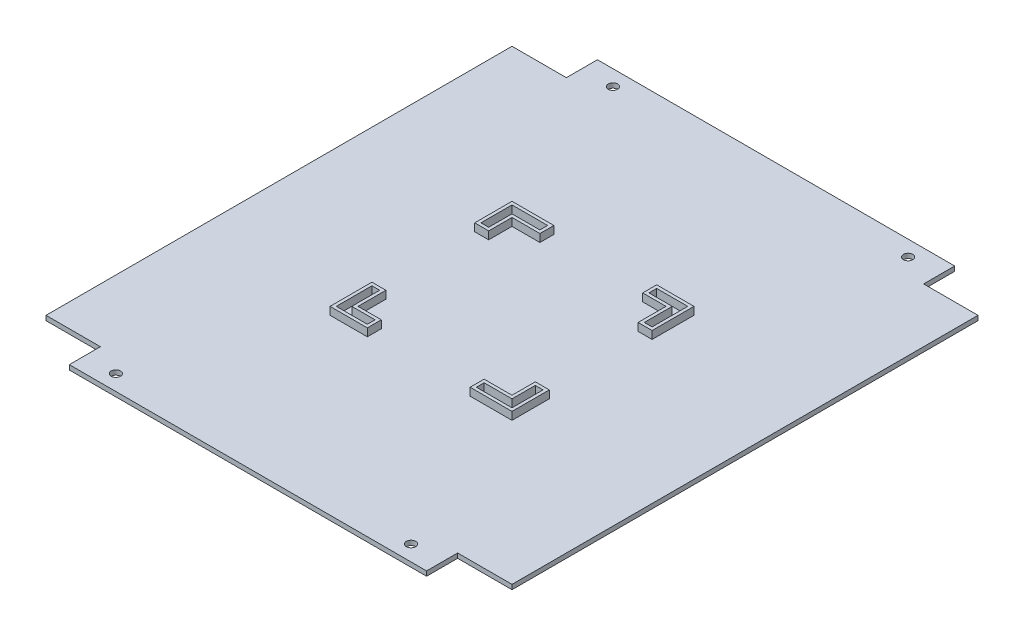
SolidWorks part; units mm, degrees
ref_plane "前视基准面" through (0, 0, 0) normal (0, 0, 1) x (1, 0, 0)
ref_plane "上视基准面" through (0, 0, 0) normal (0, 1, 0) x (1, 0, 0)
ref_plane "右视基准面" through (0, 0, 0) normal (1, 0, 0) x (0, 0, -1)
other "Configuration Table"
sketch "草图1" plane through (0, 0, 0) normal (0, 1, 0) x (1, 0, 0)
  line L0 (285, 0) -> (285, 20)
  line L1 (0, 0) -> (340, 0)
  line L2 (0, 0) -> (0, 340) construction
  line L3 (0, 340) -> (340, 340) construction
  line L4 (340, 0) -> (340, 340)
  line L5 (285, 20) -> (320, 20)
  line L6 (320, 20) -> (320, 55)
  line L7 (320, 55) -> (340, 55) construction
  line L8 (340, 55) -> (340, 0)
  line L9 (0, 170) -> (340, 170) construction
  line L10 (170, 340) -> (170, 0) construction
  line L11 (340, 0) -> (285, 0)
  line L12 (0, 0) -> (55, 0)
  line L13 (0, 55) -> (0, 0)
  line L14 (20, 55) -> (0, 55) construction
  line L15 (20, 20) -> (20, 55)
  line L16 (55, 20) -> (20, 20)
  line L17 (55, 0) -> (55, 20)
  line L18 (55, 340) -> (55, 320)
  line L19 (55, 320) -> (20, 320)
  line L20 (20, 320) -> (20, 285)
  line L21 (20, 285) -> (0, 285) construction
  line L22 (0, 285) -> (0, 340) construction
  line L23 (0, 340) -> (55, 340) construction
  line L24 (340, 340) -> (285, 340) construction
  line L25 (340, 285) -> (340, 340) construction
  line L26 (320, 285) -> (340, 285) construction
  line L27 (320, 320) -> (320, 285)
  line L28 (285, 320) -> (320, 320)
  line L29 (0, 340) -> (340, 340) construction
  line L30 (285, 340) -> (285, 320)
  line L31 (20, 285) -> (20, 55)
  line L32 (320, 285) -> (320, 55)
  line L33 (55, 340) -> (285, 340)
  dimension "D1" = 340
  dimension "D2" = 340
  dimension "D3" = 20
  dimension "D4" = 20
  dimension "D5" = 35
  dimension "D6" = 35
extrude "凸台-拉伸1" add sketch "草图1" along normal blind 3 contours L33 L18 L19 L20 L31 L15 L16 L17 L1 L0 L5 L6 L32 L27 L28 L30
sketch "草图2" plane through (0, 3, 0) normal (0, 1, 0) x (1, 0, 0)
  line L0 (55, 330) -> (285, 330) construction
  line L1 (55, 340) -> (55, 320) construction
  line L2 (285, 340) -> (285, 320) construction
  line L3 (170, 340) -> (170, 0) construction
  line L4 (55, 340) -> (285, 340) construction
  line L5 (55, 0) -> (285, 0) construction
  line L6 (20, 170) -> (320, 170) construction
  line L7 (20, 320) -> (20, 20) construction
  line L8 (320, 20) -> (320, 320) construction
  circle A0 centre (75, 330) radius 3
  circle A1 centre (265, 330) radius 3
  circle A2 centre (265, 10) radius 3
  circle A3 centre (75, 10) radius 3
  dimension "D1" = 6
  dimension "D2" = 20
extrude "切除-拉伸1" cut sketch "草图2" against normal blind 3
sketch "草图3" plane through (0, 3, 0) normal (0, 1, 0) x (1, 0, 0)
  line L0 (20, 170) -> (320, 170) construction
  line L1 (20, 320) -> (20, 20) construction
  line L2 (320, 20) -> (320, 320) construction
  line L3 (170, 340) -> (170, 0) construction
  line L4 (55, 340) -> (285, 340) construction
  line L5 (55, 0) -> (285, 0) construction
  line L6 (170, 170) -> (113.4315, 226.5685) construction
  line L7 (113.4315, 226.5685) -> (113.4315, 206.5685)
  line L8 (113.4315, 226.5685) -> (136.3812, 226.5685)
  line L15 (136.3812, 226.5685) -> (136.3812, 221.5685)
  line L16 (136.3812, 221.5685) -> (118.4315, 221.5685)
  line L17 (118.4315, 221.5685) -> (118.4315, 206.5685)
  line L18 (118.4315, 206.5685) -> (113.4315, 206.5685)
  line L19 (111.4315, 228.5685) -> (111.4315, 204.5685)
  line L20 (120.4315, 204.5685) -> (111.4315, 204.5685)
  line L21 (120.4315, 219.5685) -> (120.4315, 204.5685)
  line L22 (138.3812, 219.5685) -> (120.4315, 219.5685)
  line L23 (138.3812, 228.5685) -> (138.3812, 219.5685)
  line L24 (111.4315, 228.5685) -> (138.3812, 228.5685)
  line L25 (226.5685, 226.5685) -> (206.5685, 226.5685)
  line L26 (226.5685, 226.5685) -> (226.5685, 203.6188)
  line L27 (226.5685, 203.6188) -> (221.5685, 203.6188)
  line L28 (221.5685, 203.6188) -> (221.5685, 221.5685)
  line L29 (221.5685, 221.5685) -> (206.5685, 221.5685)
  line L30 (206.5685, 221.5685) -> (206.5685, 226.5685)
  line L31 (228.5685, 228.5685) -> (204.5685, 228.5685)
  line L32 (204.5685, 219.5685) -> (204.5685, 228.5685)
  line L33 (219.5685, 219.5685) -> (204.5685, 219.5685)
  line L34 (219.5685, 201.6188) -> (219.5685, 219.5685)
  line L35 (228.5685, 201.6188) -> (219.5685, 201.6188)
  line L36 (228.5685, 228.5685) -> (228.5685, 201.6188)
  line L37 (226.5685, 113.4315) -> (226.5685, 133.4315)
  line L38 (226.5685, 113.4315) -> (203.6188, 113.4315)
  line L39 (203.6188, 113.4315) -> (203.6188, 118.4315)
  line L40 (203.6188, 118.4315) -> (221.5685, 118.4315)
  line L41 (221.5685, 118.4315) -> (221.5685, 133.4315)
  line L42 (221.5685, 133.4315) -> (226.5685, 133.4315)
  line L43 (228.5685, 111.4315) -> (228.5685, 135.4315)
  line L44 (219.5685, 135.4315) -> (228.5685, 135.4315)
  line L45 (219.5685, 120.4315) -> (219.5685, 135.4315)
  line L46 (201.6188, 120.4315) -> (219.5685, 120.4315)
  line L47 (201.6188, 111.4315) -> (201.6188, 120.4315)
  line L48 (228.5685, 111.4315) -> (201.6188, 111.4315)
  line L49 (113.4315, 113.4315) -> (133.4315, 113.4315)
  line L50 (113.4315, 113.4315) -> (113.4315, 136.3812)
  line L51 (113.4315, 136.3812) -> (118.4315, 136.3812)
  line L52 (118.4315, 136.3812) -> (118.4315, 118.4315)
  line L53 (118.4315, 118.4315) -> (133.4315, 118.4315)
  line L54 (133.4315, 118.4315) -> (133.4315, 113.4315)
  line L55 (111.4315, 111.4315) -> (135.4315, 111.4315)
  line L56 (135.4315, 120.4315) -> (135.4315, 111.4315)
  line L57 (120.4315, 120.4315) -> (135.4315, 120.4315)
  line L58 (120.4315, 138.3812) -> (120.4315, 120.4315)
  line L59 (111.4315, 138.3812) -> (120.4315, 138.3812)
  line L60 (111.4315, 111.4315) -> (111.4315, 138.3812)
  circle A0 centre (170, 170) radius 80 construction
  dimension "D1" = 5
  dimension "D2" = 2
  dimension "D3" = 5
  dimension "D4" = 4
extrude "凸台-拉伸2" add sketch "草图3" along normal blind 5
